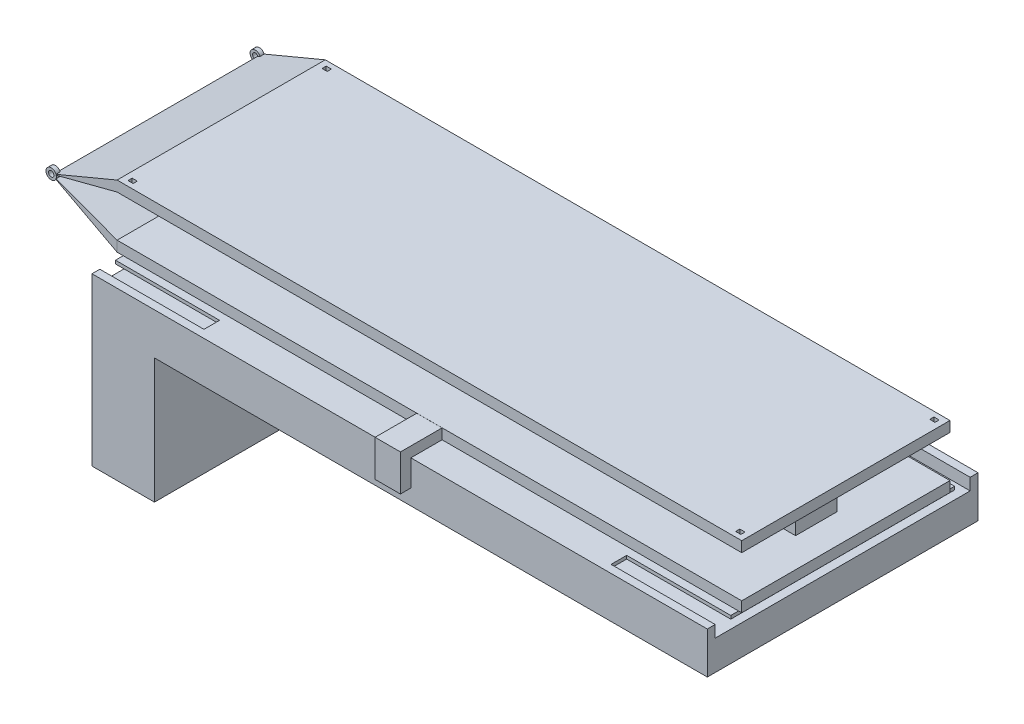
SolidWorks part; units mm, degrees
ref_plane "Front Plane" through (0, 0, 0) normal (0, 0, 1) x (1, 0, 0)
ref_plane "Top Plane" through (0, 0, 0) normal (0, 1, 0) x (1, 0, 0)
ref_plane "Right Plane" through (0, 0, 0) normal (1, 0, 0) x (0, 0, -1)
sketch "Sketch1" plane through (0, 0, 0) normal (0, 1, 0) x (1, 0, 0)
  line L1 (-381, 127) -> (381, 127)
  line L2 (-381, 127) -> (-381, -127)
  line L3 (-381, -127) -> (381, -127)
  line L4 (381, 127) -> (381, -127)
  line L5 (-381, 127) -> (381, -127) construction
  line L6 (-381, -127) -> (381, 127) construction
  point P1 (0, 0)
extrude "Boss-Extrude1" add sketch "Sketch1" along normal blind 12.7
sketch "Sketch2" plane through (0, 0, 127) normal (0, 0, 1) x (1, 0, 0)
  line L0 (-381, 12.7) -> (-461.3598, -20.9317)
  line L1 (-461.3598, -20.9317) -> (-381, 0)
  line L2 (-381, 0) -> (-381, 12.7)
extrude "Boss-Extrude2" add sketch "Sketch2" against normal up to vertex (254 mm away) up to point (-381, 12.7, -127)
sketch "Sketch5" plane through (0, 0, 127) normal (0, 0, 1) x (1, 0, 0)
  circle A0 centre (-461.3598, -20.9317) radius 3.302
  circle A1 centre (-461.3598, -20.9317) radius 6.35
sketch "Sketch9" plane through (0, 12.7, 0) normal (0, 1, 0) x (1, 0, 0)
  line L0 (-15.4208, 0) -> (15.4208, 0) construction
  line L1 (367.4986, -115.8342) -> (373.8486, -115.8342)
  line L2 (367.4986, -115.8342) -> (367.4986, -120.9142)
  line L3 (367.4986, -120.9142) -> (373.8486, -120.9142)
  line L4 (373.8486, -115.8342) -> (373.8486, -120.9142)
  line L5 (367.4986, -115.8342) -> (373.8486, -120.9142) construction
  line L6 (367.4986, -120.9142) -> (373.8486, -115.8342) construction
  line L7 (367.4986, 120.9142) -> (373.8486, 115.8342) construction
  line L8 (367.4986, 115.8342) -> (373.8486, 120.9142) construction
  line L9 (373.8486, 115.8342) -> (373.8486, 120.9142)
  line L10 (367.4986, 120.9142) -> (373.8486, 120.9142)
  line L11 (367.4986, 115.8342) -> (367.4986, 120.9142)
  line L12 (367.4986, 115.8342) -> (373.8486, 115.8342)
  line L13 (0, -15.4208) -> (0, 15.4208) construction
  line L14 (-367.4986, 115.8342) -> (-373.8486, 120.9142) construction
  line L15 (-367.4986, 120.9142) -> (-373.8486, 115.8342) construction
  line L16 (-367.4986, 115.8342) -> (-373.8486, 115.8342)
  line L17 (-367.4986, 115.8342) -> (-367.4986, 120.9142)
  line L18 (-367.4986, 120.9142) -> (-373.8486, 120.9142)
  line L19 (-373.8486, 115.8342) -> (-373.8486, 120.9142)
  line L20 (-367.4986, -120.9142) -> (-373.8486, -115.8342) construction
  line L21 (-367.4986, -115.8342) -> (-373.8486, -120.9142) construction
  line L22 (-373.8486, -115.8342) -> (-373.8486, -120.9142)
  line L23 (-367.4986, -120.9142) -> (-373.8486, -120.9142)
  line L24 (-367.4986, -115.8342) -> (-367.4986, -120.9142)
  line L25 (-367.4986, -115.8342) -> (-373.8486, -115.8342)
  point P0 (370.6736, -118.3742)
  point P12 (370.6736, 118.3742)
  point P20 (-370.6736, 118.3742)
  point P25 (-370.6736, -118.3742)
extrude "Cut-Extrude1" cut sketch "Sketch9" against normal through all
sketch "Sketch10" plane through (0, 0, 127) normal (0, 0, 1) x (1, 0, 0)
extrude "Boss-Extrude8" add sketch "Sketch5" against normal blind 5.08
sketch "Sketch13" plane through (0, 0, 0) normal (0, -1, 0) x (1, 0, 0)
  line L0 (41.91, 0) -> (-41.91, 0) construction
  line L1 (238.3726, 25.4) -> (339.9726, 25.4)
  line L2 (238.3726, 25.4) -> (238.3726, -25.4)
  line L3 (238.3726, -25.4) -> (339.9726, -25.4)
  line L4 (339.9726, 25.4) -> (339.9726, -25.4)
  line L5 (238.3726, 25.4) -> (339.9726, -25.4) construction
  line L6 (238.3726, -25.4) -> (339.9726, 25.4) construction
  point P0 (289.1726, 0)
extrude "Boss-Extrude10" add sketch "Sketch13" along normal blind 50.8
sketch "Sketch15" plane through (339.9726, 0, 0) normal (1, 0, 0) x (0, 0, -1)
  line L0 (0, 41.91) -> (0, -41.91) construction
  circle A0 centre (0, -25.4217) radius 20.32
extrude "Cut-Extrude3" cut sketch "Sketch15" against normal blind 90.17
sketch "Sketch16" plane through (339.9726, 0, 0) normal (1, 0, 0) x (0, 0, -1)
  line L0 (139.7, 0) -> (-139.7, 0) construction
  line L1 (-25.4, 0) -> (25.4, 0)
  line L2 (-25.4, 0) -> (-25.4, -50.8)
  line L3 (-25.4, -50.8) -> (25.4, -50.8)
  line L4 (25.4, 0) -> (25.4, -50.8)
  line L5 (-25.4, -50.8) -> (-25.4, 0) construction
extrude "Boss-Extrude11" add sketch "Sketch16" along normal blind 5.08
sketch "Sketch17" plane through (345.0526, 0, 0) normal (1, 0, 0) x (0, 0, -1)
  line L0 (-25.4, 0) -> (25.4, -50.8) construction
  line L1 (139.7, 0) -> (-139.7, 0) construction
  line L2 (-25.4, 0) -> (-25.4, -50.8) construction
  line L3 (25.4, -50.8) -> (25.4, 0) construction
  line L4 (-25.4, -50.8) -> (25.4, -50.8) construction
  line L5 (-25.4, -50.8) -> (25.4, 0) construction
  circle A0 centre (0, -25.4) radius 5.334
extrude "Cut-Extrude4" cut sketch "Sketch17" against normal up to next
sketch "Sketch19" plane through (238.3726, 0, 0) normal (-1, 0, 0) x (0, 0, 1)
  line L0 (0, -41.91) -> (0, 41.91) construction
  line L1 (-6.35, -6.7163) -> (6.35, -6.7163)
  line L2 (-6.35, -6.7163) -> (-6.35, -19.4163)
  line L3 (-6.35, -19.4163) -> (6.35, -19.4163)
  line L4 (6.35, -6.7163) -> (6.35, -19.4163)
  line L5 (-6.35, -6.7163) -> (6.35, -19.4163) construction
  line L6 (-6.35, -19.4163) -> (6.35, -6.7163) construction
  point P0 (0, -13.0663)
extrude "Cut-Extrude6" cut sketch "Sketch19" against normal up to next
sketch "Sketch20" plane through (0, -50.8, 0) normal (0, -1, 0) x (1, 0, 0)
  line L1 (-381, 127) -> (381, 127)
  line L2 (-381, 127) -> (-381, -127)
  line L3 (-381, -127) -> (381, -127)
  line L4 (381, 127) -> (381, -127)
  line L5 (-381, 127) -> (381, -127) construction
  line L6 (-381, -127) -> (381, 127) construction
  point P0 (0, 0)
extrude "Boss-Extrude12" add sketch "Sketch20" along normal blind 12.7
sketch "Sketch12" plane through (0, 0, -127) normal (0, 0, -1) x (-1, 0, 0)
  circle A0 centre (461.3598, -20.9317) radius 3.302
  circle A1 centre (461.3598, -20.9317) radius 6.35
mirror "Mirror1" about plane through (0, 0, 0) normal (0, 0, 1) of "Boss-Extrude8"
sketch "Sketch22" plane through (0, 0, 127) normal (0, 0, 1) x (1, 0, 0)
  line L0 (-381, -50.8) -> (-461.3598, -20.9317)
  line L1 (-461.3598, -20.9317) -> (-381, -63.5)
  line L2 (-381, -63.5) -> (-381, -50.8)
extrude "Boss-Extrude15" add sketch "Sketch22" against normal up to vertex (254 mm away) separate body up to point (-461.3598, -20.9317, -127)
sketch "Sketch23" plane through (0, 0, 127) normal (0, 0, 1) x (1, 0, 0)
  circle A0 centre (-461.3598, -20.9317) radius 3.302
extrude "Cut-Extrude7" cut sketch "Sketch23" against normal through all
sketch "Sketch24" plane through (0, -63.5, 0) normal (0, -1, 0) x (1, 0, 0)
  line L0 (41.91, 0) -> (-41.91, 0) construction
  line L1 (-373.4876, 165.1) -> (377.1051, 165.1)
  line L2 (-373.4876, 165.1) -> (-373.4876, -165.1)
  line L3 (-373.4876, -165.1) -> (377.1051, -165.1)
  line L4 (377.1051, 165.1) -> (377.1051, -165.1)
  line L5 (-373.4876, 165.1) -> (377.1051, -165.1) construction
  line L6 (-373.4876, -165.1) -> (377.1051, 165.1) construction
  point P0 (1.8088, 0)
extrude "Boss-Extrude16" add sketch "Sketch24" along normal blind 50.8
sketch "Sketch28" plane through (0, -114.3, 0) normal (0, -1, 0) x (1, 0, 0)
  line L0 (-373.4876, -165.1) -> (377.1051, -165.1) construction
  line L1 (-373.4876, 165.1) -> (-297.2876, 165.1)
  line L2 (-373.4876, 165.1) -> (-373.4876, -165.1)
  line L3 (-373.4876, -165.1) -> (-297.2876, -165.1)
  line L4 (-297.2876, 165.1) -> (-297.2876, -165.1)
extrude "Boss-Extrude17" add sketch "Sketch28" along normal blind 152.4
extrude "Boss-Extrude9" add sketch "Sketch12" against normal blind 5.08
sketch "Sketch29" plane through (238.3726, 0, 0) normal (-1, 0, 0) x (0, 0, 1)
  line L0 (0, -153.67) -> (0, 153.67) construction
  line L1 (-12.7, -0.4389) -> (12.7, -0.4389)
  line L2 (-12.7, -0.4389) -> (-12.7, -25.8389)
  line L3 (-12.7, -25.8389) -> (12.7, -25.8389)
  line L4 (12.7, -0.4389) -> (12.7, -25.8389)
  line L5 (-12.7, -0.4389) -> (12.7, -25.8389) construction
  line L6 (-12.7, -25.8389) -> (12.7, -0.4389) construction
  point P0 (0, -13.1389)
extrude "Boss-Extrude18" add sketch "Sketch29" along normal blind 50.8
sketch "Sketch30" plane through (0, -50.8, 0) normal (0, 1, 0) x (1, 0, 0)
  line L0 (-153.67, 0) -> (153.67, 0) construction
  line L1 (180.5558, 12.7) -> (205.9558, 12.7)
  line L2 (180.5558, 12.7) -> (180.5558, -12.7)
  line L3 (180.5558, -12.7) -> (205.9558, -12.7)
  line L4 (205.9558, 12.7) -> (205.9558, -12.7)
  line L5 (180.5558, 12.7) -> (205.9558, -12.7) construction
  line L6 (180.5558, -12.7) -> (205.9558, 12.7) construction
  point P0 (193.2558, 0)
  point P7 (193.2558, 0)
extrude "Boss-Extrude19" add sketch "Sketch30" along normal up to surface (50.8 mm away)
sketch "Sketch31" plane through (0, 0, 127) normal (0, 0, 1) x (1, 0, 0)
  line L0 (0, -153.67) -> (0, 153.67) construction
  line L1 (-15.4635, -50.8958) -> (15.4635, -50.8958)
  line L2 (-15.4635, -50.8958) -> (-15.4635, -95.3747)
  line L3 (-15.4635, -95.3747) -> (15.4635, -95.3747)
  line L4 (15.4635, -50.8958) -> (15.4635, -95.3747)
  line L5 (-15.4635, -50.8958) -> (15.4635, -95.3747) construction
  line L6 (-15.4635, -95.3747) -> (15.4635, -50.8958) construction
  point P0 (0, -73.1353)
  point P7 (0, -73.1353)
extrude "Boss-Extrude20" add sketch "Sketch31" along normal blind 50.8
sketch "Sketch25" plane through (-373.4876, 0, 0) normal (-1, 0, 0) x (0, 0, 1)
  line L0 (0, -153.67) -> (0, 153.67) construction
  line L1 (-155.5171, -67.4497) -> (155.5171, -67.4497)
  line L2 (-155.5171, -67.4497) -> (-155.5171, -77.9143)
  line L3 (-155.5171, -77.9143) -> (155.5171, -77.9143)
  line L4 (155.5171, -67.4497) -> (155.5171, -77.9143)
  line L5 (-155.5171, -67.4497) -> (155.5171, -77.9143) construction
  line L6 (-155.5171, -77.9143) -> (155.5171, -67.4497) construction
  point P0 (0, -72.682)
extrude "Cut-Extrude8" cut sketch "Sketch25" against normal through all
sketch "Sketch32" plane through (-373.4876, 0, 0) normal (-1, 0, 0) x (0, 0, 1)
  line L1 (155.5171, -67.4497) -> (136.4671, -67.4497)
  line L2 (155.5171, -67.4497) -> (155.5171, -53.2082)
  line L3 (155.5171, -53.2082) -> (136.4671, -53.2082)
  line L4 (136.4671, -67.4497) -> (136.4671, -53.2082)
  line L5 (-155.5171, -67.4497) -> (-136.4671, -67.4497)
  line L6 (-155.5171, -67.4497) -> (-155.5171, -53.2082)
  line L7 (-155.5171, -53.2082) -> (-136.4671, -53.2082)
  line L8 (-136.4671, -67.4497) -> (-136.4671, -53.2082)
extrude "Cut-Extrude9" cut sketch "Sketch32" against normal blind 127
sketch "Sketch33" plane through (377.1051, 0, 0) normal (1, 0, 0) x (0, 0, -1)
  line L1 (-155.5171, -67.4497) -> (-136.4671, -67.4497)
  line L2 (-155.5171, -67.4497) -> (-155.5171, -43.8313)
  line L3 (-155.5171, -43.8313) -> (-136.4671, -43.8313)
  line L4 (-136.4671, -67.4497) -> (-136.4671, -43.8313)
  line L5 (155.5171, -67.4497) -> (136.4671, -67.4497)
  line L6 (155.5171, -67.4497) -> (155.5171, -53.2082)
  line L7 (155.5171, -53.2082) -> (136.4671, -53.2082)
  line L8 (136.4671, -67.4497) -> (136.4671, -53.2082)
extrude "Cut-Extrude10" cut sketch "Sketch33" against normal blind 127
